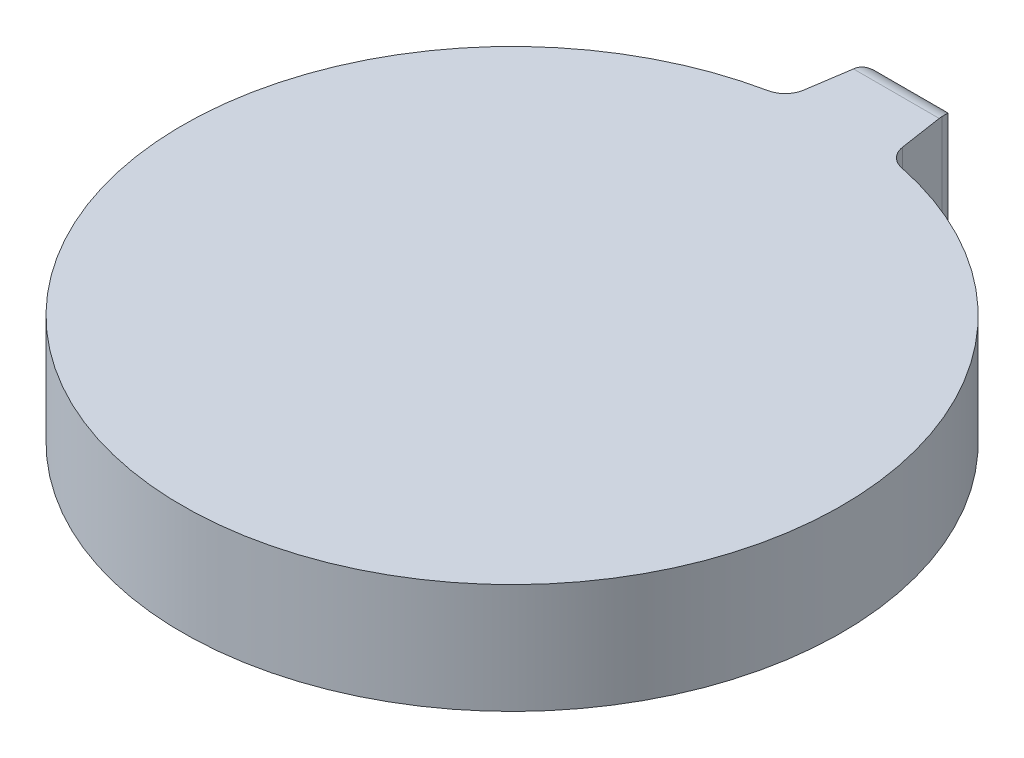
SolidWorks part; units mm, degrees
ref_plane "Front Plane" through (0, 0, 0) normal (0, 0, 1) x (1, 0, 0)
ref_plane "Top Plane" through (0, 0, 0) normal (0, 1, 0) x (1, 0, 0)
ref_plane "Right Plane" through (0, 0, 0) normal (1, 0, 0) x (0, 0, -1)
sketch "Sketch1" plane through (0, 0, 0) normal (0, 1, 0) x (1, 0, 0)
  circle A0 centre (0, 0) radius 19.05
  dimension "D1" = 38.1
extrude "Boss-Extrude1" add sketch "Sketch1" along normal blind 6.35
sketch "Sketch2" plane through (0, 0, 0) normal (0, 1, 0) x (1, 0, 0)
  line L0 (-2.9921, 18.8136) -> (-2.286, 23.4801)
  line L1 (2.9921, 18.8136) -> (2.286, 23.4801)
  line L2 (-2.286, 23.4801) -> (2.286, 23.4801)
  line L3 (-2.9921, 18.8136) -> (2.9921, 18.8136)
  circle A1 centre (0, 0) radius 19.05 construction
  point P0 (0, 19.05)
  point P1 (2.9921, 18.8136)
  point P4 (-2.9921, 18.8136)
  dimension "D1" = 2.9921
  dimension "D2" = 2.9921
  dimension "D3" = 4.572
  dimension "D4" = 4.6666
  dimension "D5" = 4.6666
extrude "Boss-Extrude2" add sketch "Sketch2" along normal blind 6.35 contours L0 L2 L1 L3
fillet "Fillet13" radius 1.27 4 edges at (2.286, 3.175, -23.4801) (0, 0, -23.4801) (0, 6.35, -23.4801) (-2.286, 3.175, -23.4801)
fillet "Fillet15" radius 1.27 2 edges at (-2.9921, 3.175, -18.8136) (2.9921, 3.175, -18.8136)
